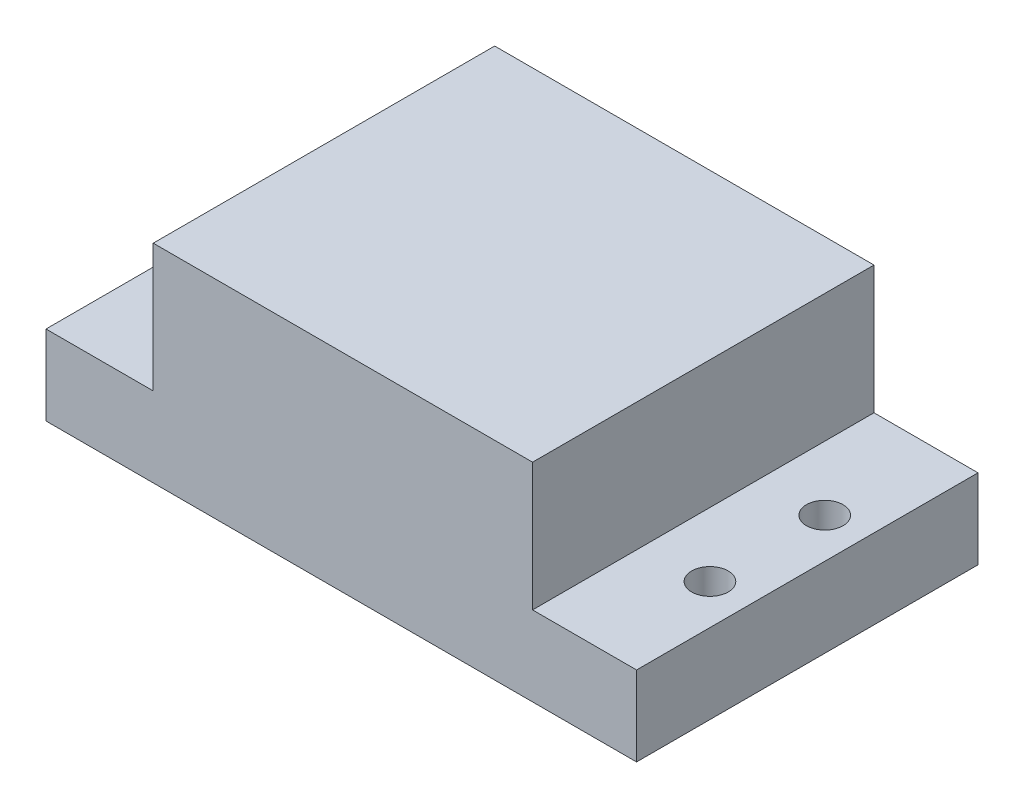
SolidWorks part; units mm, degrees
ref_plane "Front Plane" through (0, 0, 0) normal (0, 0, 1) x (1, 0, 0)
ref_plane "Top Plane" through (0, 0, 0) normal (0, 1, 0) x (1, 0, 0)
ref_plane "Right Plane" through (0, 0, 0) normal (1, 0, 0) x (0, 0, -1)
sketch "Sketch1" plane through (0, 0, 0) normal (0, 1, 0) x (1, 0, 0)
  line L1 (-35.9407, 10.0725) -> (44.8313, 10.0725)
  line L2 (-35.9407, 10.0725) -> (-35.9407, -36.6275)
  line L3 (-35.9407, -36.6275) -> (44.8313, -36.6275)
  line L4 (44.8313, 10.0725) -> (44.8313, -36.6275)
  dimension "D1" = 46.7
  dimension "D2" = 80.772
extrude "Boss-Extrude1" add sketch "Sketch1" along normal blind 10.9
sketch "Sketch3" plane through (0, 10.9, 0) normal (0, 1, 0) x (1, 0, 0)
  line L0 (44.8313, 10.0725) -> (-35.9407, 10.0725) construction
  line L1 (-35.9407, -36.6275) -> (44.8313, -36.6275) construction
  line L2 (-35.9407, 10.0725) -> (-35.9407, -36.6275) construction
  line L3 (44.8313, 10.0725) -> (-35.9407, 10.0725) construction
  line L4 (44.8313, -36.6275) -> (44.8313, 10.0725) construction
  line L5 (-35.9407, -36.6275) -> (44.8313, -36.6275) construction
  circle A0 centre (-30.4797, -5.4275) radius 2.5
  circle A1 centre (-30.4797, -21.1275) radius 2.5
  circle A2 centre (39.3703, -5.4275) radius 2.5
  circle A3 centre (39.3703, -21.1275) radius 2.5
  dimension "D1" = 15.5
  dimension "D2" = 15.5
  dimension "D5" = 15.5
  dimension "D7" = 5.461
  dimension "D3" = 5.461
  dimension "D4" = 5.461
  dimension "D6" = 5.461
  dimension "D8" = 15.5
extrude "Cut-Extrude1" cut sketch "Sketch3" against normal up to surface (10.9 mm away) up to face at (4.4453, 0, 13.2775)
sketch "Sketch8" plane through (0, 10.9, 0) normal (0, 1, 0) x (1, 0, 0)
  line L1 (44.8313, 10.0725) -> (-35.9407, 10.0725) construction
  line L3 (30.6073, 10.0725) -> (30.6073, -36.6275)
  line L4 (30.6073, 10.0725) -> (-21.2732, 10.0725)
  line L5 (30.6073, -36.6275) -> (-21.2732, -36.6275)
  line L6 (-21.2732, 10.0725) -> (-21.2732, -36.6275)
  line L7 (-35.9407, -36.6275) -> (44.8313, -36.6275) construction
extrude "Boss-Extrude2" add sketch "Sketch8" along normal blind 17.5
